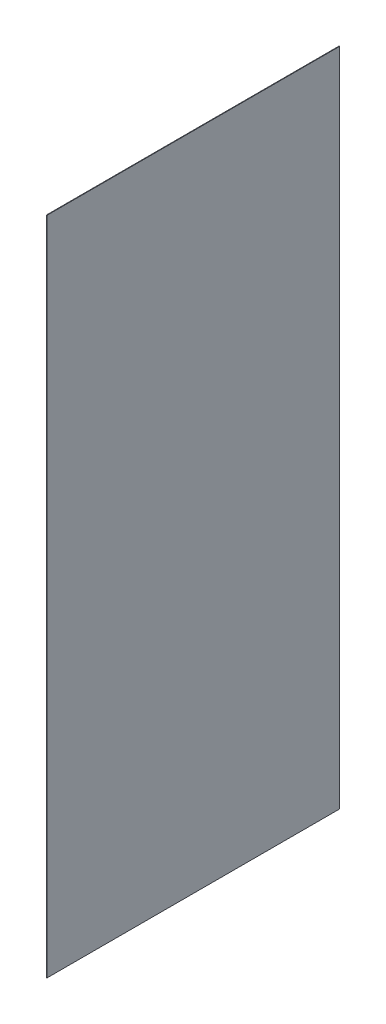
SolidWorks part; units mm, degrees
ref_plane "Front Plane" through (0, 0, 0) normal (0, 0, 1) x (1, 0, 0)
ref_plane "Top Plane" through (0, 0, 0) normal (0, 1, 0) x (1, 0, 0)
ref_plane "Right Plane" through (0, 0, 0) normal (1, 0, 0) x (0, 0, -1)
other "Configuration Table"
sketch "Sketch1" plane through (0, 0, 0) normal (0, 0, 1) x (1, 0, 0)
  line L1 (0, 120) -> (1.5, 120)
  line L2 (0, 120) -> (0, 1970)
  line L3 (0, 1970) -> (1.5, 1970)
  line L4 (1.5, 120) -> (1.5, 1970)
extrude "PRESS_dis_yan_sol_1" add sketch "Sketch1" against normal blind 820 separate body
